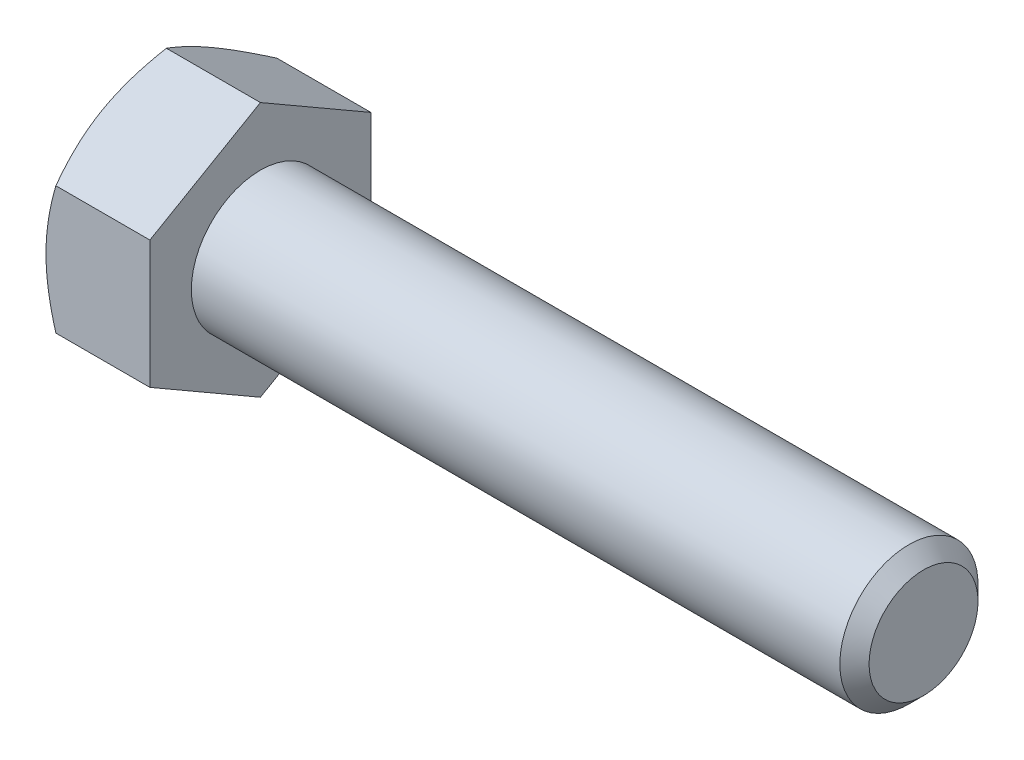
SolidWorks part; units mm, degrees
extrude "BaseHead" add sketch "Sketch1" along normal blind 5.969
sketch "Sketch1" plane through (0, 0, 0) normal (1, 0, 0) x (0, 0, -1)
  line L0 (6.35, 3.6662) -> (6.35, -3.6662)
  line L1 (-6.35, 3.6662) -> (-6.35, -3.6662)
  line L2 (6.35, -3.6662) -> (0, -7.3323)
  line L3 (0, -7.3323) -> (-6.35, -3.6662)
  line L4 (6.35, 3.6662) -> (0, 7.3323)
  line L5 (0, 7.3323) -> (-6.35, 3.6662)
  dimension "Width_flats" = 12.7
  dimension "D2" = 120
  dimension "D3" = 6.35
  dimension "D4" = 6.35
  dimension "D5" = 6.35
ref_plane "Plane1" through (0, 0, 0) normal (0, 0, 1) x (1, 0, 0)
ref_plane "Plane2" through (0, 0, 0) normal (0, 1, 0) x (1, 0, 0)
ref_plane "Plane3" through (0, 0, 0) normal (1, 0, 0) x (0, 0, -1)
other "Configuration Table"
sketch "BodySke" plane through (0, 0, 0) normal (0, 0, 1) x (1, 0, 0)
  line L0 (0, 3.6662) -> (0, -3.6662) construction
  line L1 (0, 0) -> (44.069, 0)
  line L2 (0, 0) -> (0, 3.9688)
  line L3 (0, 3.9688) -> (43.2295, 3.9688)
  line L4 (44.069, 0) -> (44.069, 3.1293)
  line L5 (5.969, 7.3323) -> (5.969, 3.6662) construction
  line L6 (44.069, 3.1293) -> (43.2295, 3.9688)
  line L7 (0, 0) -> (96.52, 0) construction
  line L8 (44.069, -3.1293) -> (43.2295, -3.9688) construction
  line L9 (0, -3.9688) -> (43.2295, -3.9688) construction
  line L10 (7.3787, 15.24) -> (7.3787, -2.54) construction
  line L11 (21.844, 15.24) -> (21.844, -2.54) construction
  line L12 (5.969, 3.6662) -> (5.969, -3.6662) construction
  dimension "Diameter" = 7.9375
revolve "BaseBody" add sketch "BodySke" angle 360 about L7
cosmetic thread "ThreadCosmetic" [suppressed] parameters "Thread_length"=22.225, "Thread_minor"=6.2586
sketch "Sketch3" plane through (0, 0, 0) normal (0, 0, 1) x (1, 0, 0)
  line L0 (0, 6.35) -> (4.2333, 13.6823)
  line L1 (0, 7.3323) -> (0, 3.6662) construction
  line L2 (4.2333, 13.6823) -> (4.2333, 20.0323)
  line L3 (4.2333, 20.0323) -> (-12.7, 20.0323)
  line L4 (-12.7, 20.0323) -> (-12.7, 6.35)
  line L5 (-12.7, 6.35) -> (0, 6.35)
  line L6 (0, 0) -> (99.06, 0) construction
  line L7 (5.969, 7.3323) -> (0, 7.3323) construction
  dimension "D4" = 6.35
  dimension "D1" = 6.35
  dimension "D2" = 6.35
  dimension "D3" = 12.7
  dimension "Head_ch_ang" = 30
revolve "HeadChamfer" cut sketch "Sketch3" angle 360 about L6
fillet "HeadFillet" [suppressed] radius 0.762
sketch "ThdSchSke" plane through (0, 0, 0) normal (0, 0, 1) x (1, 0, 0)
  line L0 (21.844, -3.1293) -> (21.2562, -3.9687)
  line L1 (21.844, -3.1293) -> (22.4318, -3.9688)
  line L2 (22.4318, -3.9688) -> (22.4318, -4.9609)
  line L3 (-3.175, 0) -> (5.1513, 0) construction
  line L5 (22.4318, -4.9609) -> (21.2562, -4.9609)
  line L6 (21.2562, -4.9609) -> (21.2562, -3.9687)
  dimension "Thread_minor" = 6.2586
  dimension "Diameter" = 7.9375
  dimension "Start" = 21.844
revolve "ThreadSchematic" [suppressed] cut sketch "ThdSchSke" angle 360 about L3
pattern_linear "ThdSchPat" [suppressed]
equation "\"D3@Sketch1\" = \"Width_flats@Sketch1\" / 2"
equation "\"D4@Sketch1\" = \"D3@Sketch1\""
equation "\"D5@Sketch1\" = \"D4@Sketch1\""
equation "\"Thread_minor@ThreadCosmetic\" = \"Minor_dia@BodySke\""
equation "\"D1@Sketch3\" = \"Width_flats@Sketch1\" / 2"
equation "\"Thread_length@ThreadCosmetic\" = ((sgn( (\"Length@BodySke\" - \"Advance@BodySke\" ) - \"Thread_nom@BodySke\" )-1)*( (\"Length@BodySke\" - \"Advance@BodySke\" ) - \"Thread_nom@BodySke\" ))/-2+ \"Thread_nom@BodySke\""
equation "\"Thread_minor@ThdSchSke\" = \"Minor_dia@BodySke\""
equation "\"Diameter@ThdSchSke\" = \"Diameter@BodySke\""
equation "\"Overcut@ThdSchSke\" = \"Diameter@BodySke\" * 1.25"
equation "\"Start@ThdSchSke\" = \"Head_ht@BaseHead\" + \"Length@BodySke\" - \"Thread_length@ThreadCosmetic\"  '---Non-countersunk---"
equation "\"Num_threads@ThdSchPat\" = int( \"Thread_length@ThreadCosmetic\" / \"Advance@BodySke\" + 0.999 )  + 1"
equation "\"Advance@ThdSchPat\" = \"Thread_length@ThreadCosmetic\" /  (\"Num_threads@ThdSchPat\" - 1) 'relax it"
equation "\"Num_threads@ThdSchPat\" = \"Num_threads@ThdSchPat\" - sgn( \"Num_threads@ThdSchPat\" - 1) '---chamfered tips only---"
